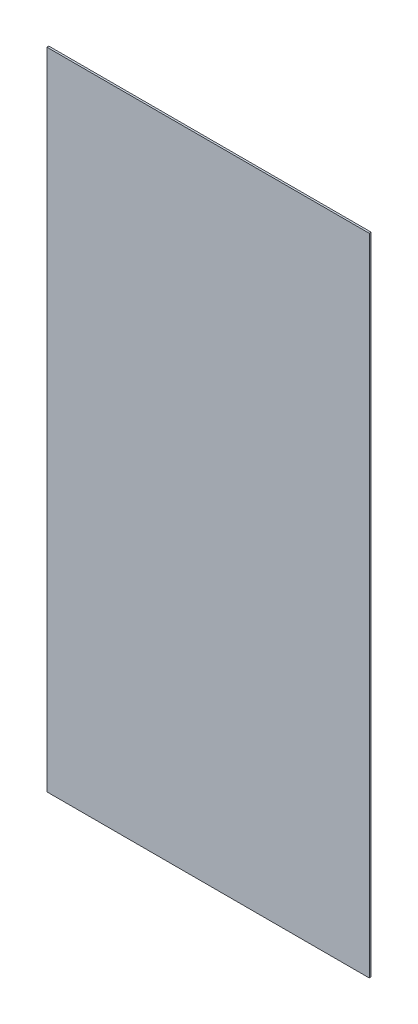
SolidWorks part; units mm, degrees
material "Malleable Cast Iron"
ref_plane "Front Plane" through (0, 0, 0) normal (0, 0, 1) x (1, 0, 0)
ref_plane "Top Plane" through (0, 0, 0) normal (0, 1, 0) x (1, 0, 0)
ref_plane "Right Plane" through (0, 0, 0) normal (1, 0, 0) x (0, 0, -1)
sketch "Sketch1" plane through (0, 0, 0) normal (0, 0, 1) x (1, 0, 0)
  line L1 (-250, 500) -> (250, 500)
  line L2 (-250, 500) -> (-250, -500)
  line L3 (-250, -500) -> (250, -500)
  line L4 (250, 500) -> (250, -500)
  line L5 (-250, 500) -> (250, -500) construction
  line L6 (-250, -500) -> (250, 500) construction
  point P0 (0, 0)
  dimension "D1" = 1000
  dimension "D2" = 500
extrude "Boss-Extrude1" add sketch "Sketch1" along normal blind 3
